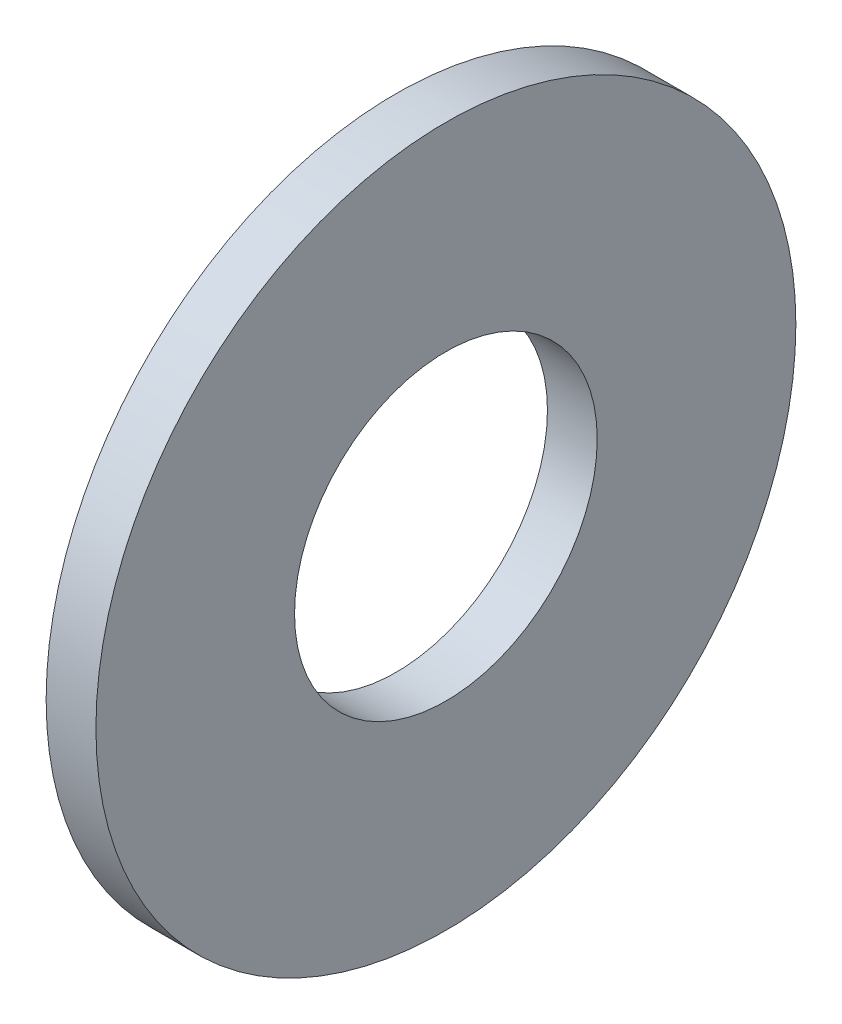
SolidWorks part; units mm, degrees
ref_plane "Plane1" through (0, 0, 0) normal (0, 0, 1) x (1, 0, 0)
ref_plane "Plane2" through (0, 0, 0) normal (0, 1, 0) x (1, 0, 0)
ref_plane "Plane3" through (0, 0, 0) normal (1, 0, 0) x (0, 0, -1)
sketch "Sketch1" plane through (0, 0, 0) normal (0, 0, 1) x (1, 0, 0)
  line L0 (-34.925, 0) -> (9.525, 0) construction
  line L1 (0, 19.46) -> (0, 45)
  line L2 (0, 45) -> (-6.4, 45)
  line L3 (-6.4, 45) -> (-6.4, 19.46)
  line L4 (-6.4, 19.46) -> (0, 19.46)
  dimension "Thickness" = 6.4
  dimension "Inside_dia" = 38.92
  dimension "Outside_dia" = 90
revolve "Base-Revolve" add sketch "Sketch1" angle 360 about L0
